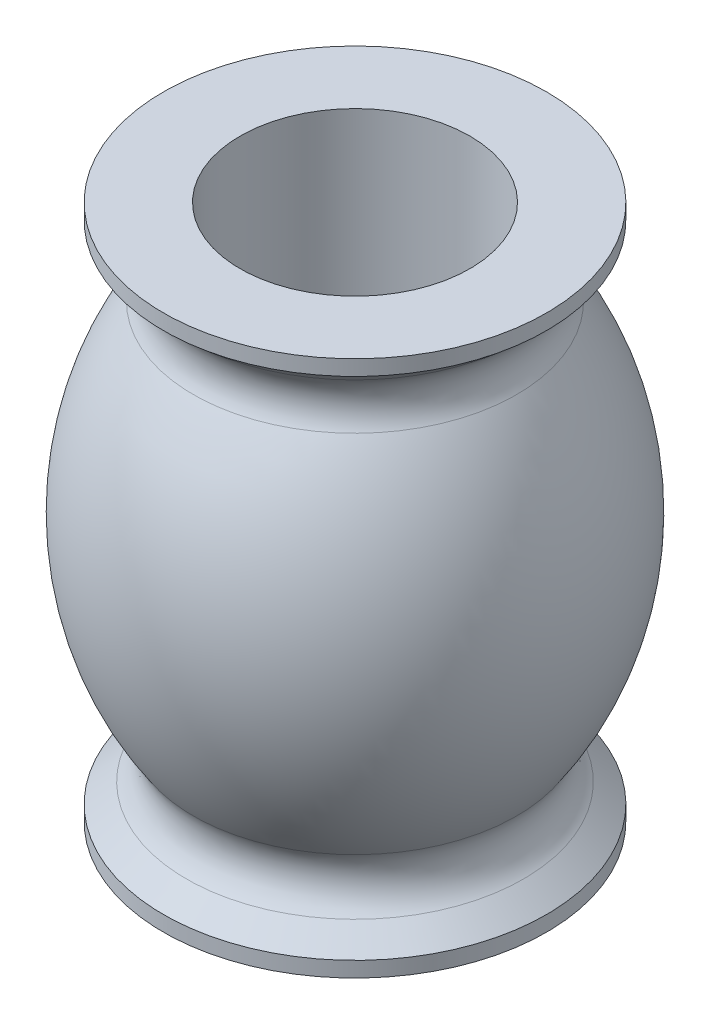
SolidWorks part; units mm, degrees
ref_plane "前视基准面" through (0, 0, 0) normal (0, 0, 1) x (1, 0, 0)
ref_plane "上视基准面" through (0, 0, 0) normal (0, 1, 0) x (1, 0, 0)
ref_plane "右视基准面" through (0, 0, 0) normal (1, 0, 0) x (0, 0, -1)
sketch "草图1" plane through (0, 0, 0) normal (0, 0, 1) x (1, 0, 0)
  line L0 (2.5, 3.5) -> (1.5, 3.5)
  line L1 (1.5, 3.5) -> (1.5, -3.5)
  line L2 (1.5, -3.5) -> (2.5, -3.5)
  line L3 (2.5, -3.5) -> (2.5, -3.3)
  line L4 (2.5, -3.3) -> (2.1999, -3.0482)
  line L5 (2.1999, 3.0482) -> (2.5, 3.3)
  line L6 (2.5, 3.3) -> (2.5, 3.5)
  line L7 (0, 3.5) -> (0, -3.5) construction
  arc A0 (2.1999, -3.0482) -> (2.1095, -2.3816) centre (2.5213, -2.6652) cw
  arc A1 (2.1095, -2.3816) -> (2.1095, 2.3816) centre (-1.35, 0) ccw
  arc A2 (2.1095, 2.3816) -> (2.1999, 3.0482) centre (2.5213, 2.6652) cw
revolve "旋转1" add sketch "草图1" angle 360 about L7
